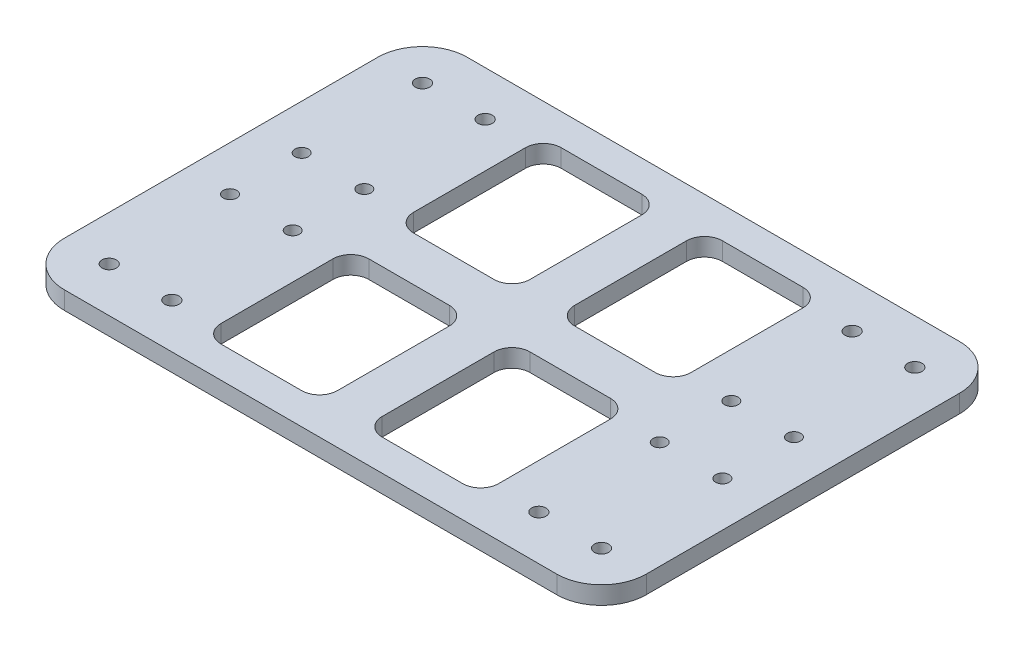
SolidWorks part; units mm, degrees
ref_plane "Front Plane" through (0, 0, 0) normal (0, 0, 1) x (1, 0, 0)
ref_plane "Top Plane" through (0, 0, 0) normal (0, 1, 0) x (1, 0, 0)
ref_plane "Right Plane" through (0, 0, 0) normal (1, 0, 0) x (0, 0, -1)
sketch "Sketch2" plane through (0, 0, 0) normal (0, 1, 0) x (1, 0, 0)
  line L1 (6.2712, 10.565) -> (136.2712, 10.565)
  line L2 (6.2712, 10.565) -> (6.2712, 100.565)
  line L3 (6.2712, 100.565) -> (136.2712, 100.565)
  line L4 (136.2712, 10.565) -> (136.2712, 100.565)
  dimension "D1" = 130
  dimension "D2" = 90
extrude "Boss-Extrude1" add sketch "Sketch2" against normal blind 4
sketch "Sketch3" plane through (0, 0, 0) normal (0, 1, 0) x (1, 0, 0)
  line L0 (71.2712, 100.565) -> (71.2712, 10.565) construction
  line L1 (136.2712, 100.565) -> (6.2712, 100.565) construction
  line L2 (6.2712, 10.565) -> (136.2712, 10.565) construction
  line L3 (6.2712, 55.565) -> (136.2712, 55.565) construction
  line L4 (6.2712, 100.565) -> (6.2712, 10.565) construction
  line L5 (136.2712, 10.565) -> (136.2712, 100.565) construction
  line L7 (112.2712, 63.565) -> (126.2712, 63.565) construction
  line L8 (112.2712, 63.565) -> (112.2712, 47.565) construction
  line L9 (112.2712, 47.565) -> (126.2712, 47.565) construction
  line L10 (126.2712, 63.565) -> (126.2712, 47.565) construction
  circle A0 centre (126.2712, 63.565) radius 1.5
  circle A1 centre (126.2712, 47.565) radius 1.5
  circle A2 centre (112.2712, 47.565) radius 1.5
  circle A3 centre (112.2712, 63.565) radius 1.5
  circle A4 centre (16.2712, 47.565) radius 1.5
  circle A5 centre (30.2712, 47.565) radius 1.5
  circle A6 centre (16.2712, 63.565) radius 1.5
  circle A7 centre (30.2712, 63.565) radius 1.5
  point P16 (112.2712, 55.565)
  dimension "D4" = 3
  dimension "D1" = 14
  dimension "D2" = 16
  dimension "D3" = 10
extrude "Cut-Extrude1" cut sketch "Sketch3" against normal blind 10 contours A6 | A7 | A4 | A5 | A0 | A3 | A2 | A1
sketch "Sketch4" plane through (0, 0, 0) normal (0, 1, 0) x (1, 0, 0)
  line L0 (16.2712, 47.565) -> (16.2712, 10.565) construction
  line L1 (6.2712, 10.565) -> (136.2712, 10.565) construction
  line L2 (30.2712, 47.565) -> (30.2712, 10.565) construction
  line L3 (6.2712, 55.565) -> (136.2712, 55.565) construction
  line L4 (136.2712, 100.565) -> (6.2712, 100.565) construction
  line L5 (6.2712, 100.565) -> (6.2712, 10.565) construction
  line L6 (71.2712, 100.565) -> (71.2712, 10.565) construction
  line L7 (16.2712, 20.565) -> (71.2712, 20.565) construction
  line L8 (136.2712, 10.565) -> (136.2712, 100.565) construction
  circle A0 centre (16.2712, 20.565) radius 1.6
  circle A1 centre (30.2712, 20.565) radius 1.6
  circle A2 centre (30.2712, 90.565) radius 1.6
  circle A3 centre (16.2712, 90.565) radius 1.6
  circle A4 centre (112.2712, 20.565) radius 1.6
  circle A5 centre (126.2712, 20.565) radius 1.6
  circle A6 centre (126.2712, 90.565) radius 1.6
  circle A7 centre (112.2712, 90.565) radius 1.6
  point P23 (30.2712, 20.565)
  dimension "D2" = 3.2
  dimension "D1" = 10
extrude "Cut-Extrude2" cut sketch "Sketch4" against normal blind 10
fillet "Fillet1" radius 10 4 edges at (136.2712, -2, -100.565) (6.2712, -2, -100.565) (6.2712, -2, -10.565) (136.2712, -2, -10.565)
sketch "Sketch5" plane through (0, 0, 0) normal (0, 1, 0) x (1, 0, 0)
  line L0 (71.2712, 100.565) -> (71.2712, 10.565) construction
  line L1 (126.2712, 100.565) -> (16.2712, 100.565) construction
  line L2 (16.2712, 10.565) -> (126.2712, 10.565) construction
  line L3 (6.2712, 55.565) -> (136.2712, 55.565) construction
  line L4 (6.2712, 90.565) -> (6.2712, 20.565) construction
  line L5 (136.2712, 20.565) -> (136.2712, 90.565) construction
  line L6 (76.2712, 89.565) -> (76.2712, 64.565)
  line L7 (80.2712, 60.565) -> (98.2712, 60.565)
  line L9 (80.2712, 93.565) -> (98.2712, 93.565)
  line L10 (102.2712, 89.565) -> (102.2712, 64.565)
  line L11 (40.2712, 89.565) -> (40.2712, 64.565)
  line L12 (62.2712, 93.565) -> (44.2712, 93.565)
  line L13 (62.2712, 60.565) -> (44.2712, 60.565)
  line L14 (66.2712, 89.565) -> (66.2712, 64.565)
  line L15 (66.2712, 21.565) -> (66.2712, 46.565)
  line L16 (62.2712, 50.565) -> (44.2712, 50.565)
  line L17 (62.2712, 17.565) -> (44.2712, 17.565)
  line L18 (40.2712, 21.565) -> (40.2712, 46.565)
  line L19 (102.2712, 21.565) -> (102.2712, 46.565)
  line L20 (80.2712, 17.565) -> (98.2712, 17.565)
  line L21 (80.2712, 50.565) -> (98.2712, 50.565)
  line L22 (76.2712, 21.565) -> (76.2712, 46.565)
  circle A0 centre (112.2712, 90.565) radius 1.6 construction
  arc A1 (102.2712, 89.565) -> (98.2712, 93.565) centre (98.2712, 89.565) ccw
  arc A2 (102.2712, 64.565) -> (98.2712, 60.565) centre (98.2712, 64.565) cw
  arc A3 (80.2712, 60.565) -> (76.2712, 64.565) centre (80.2712, 64.565) cw
  arc A4 (76.2712, 89.565) -> (80.2712, 93.565) centre (80.2712, 89.565) cw
  arc A5 (66.2712, 89.565) -> (62.2712, 93.565) centre (62.2712, 89.565) ccw
  arc A6 (62.2712, 60.565) -> (66.2712, 64.565) centre (62.2712, 64.565) ccw
  arc A7 (40.2712, 64.565) -> (44.2712, 60.565) centre (44.2712, 64.565) ccw
  arc A8 (40.2712, 89.565) -> (44.2712, 93.565) centre (44.2712, 89.565) cw
  arc A9 (40.2712, 21.565) -> (44.2712, 17.565) centre (44.2712, 21.565) ccw
  arc A10 (40.2712, 46.565) -> (44.2712, 50.565) centre (44.2712, 46.565) cw
  arc A11 (62.2712, 50.565) -> (66.2712, 46.565) centre (62.2712, 46.565) cw
  arc A12 (66.2712, 21.565) -> (62.2712, 17.565) centre (62.2712, 21.565) cw
  arc A13 (76.2712, 21.565) -> (80.2712, 17.565) centre (80.2712, 21.565) ccw
  arc A14 (80.2712, 50.565) -> (76.2712, 46.565) centre (80.2712, 46.565) ccw
  arc A15 (102.2712, 46.565) -> (98.2712, 50.565) centre (98.2712, 46.565) ccw
  arc A16 (102.2712, 21.565) -> (98.2712, 17.565) centre (98.2712, 21.565) cw
  point P14 (96.5523, 94.5712)
  dimension "D5" = 4
  dimension "D1" = 5
  dimension "D2" = 5
  dimension "D3" = 10
  dimension "D4" = 7
extrude "Cut-Extrude3" cut sketch "Sketch5" against normal blind 10
